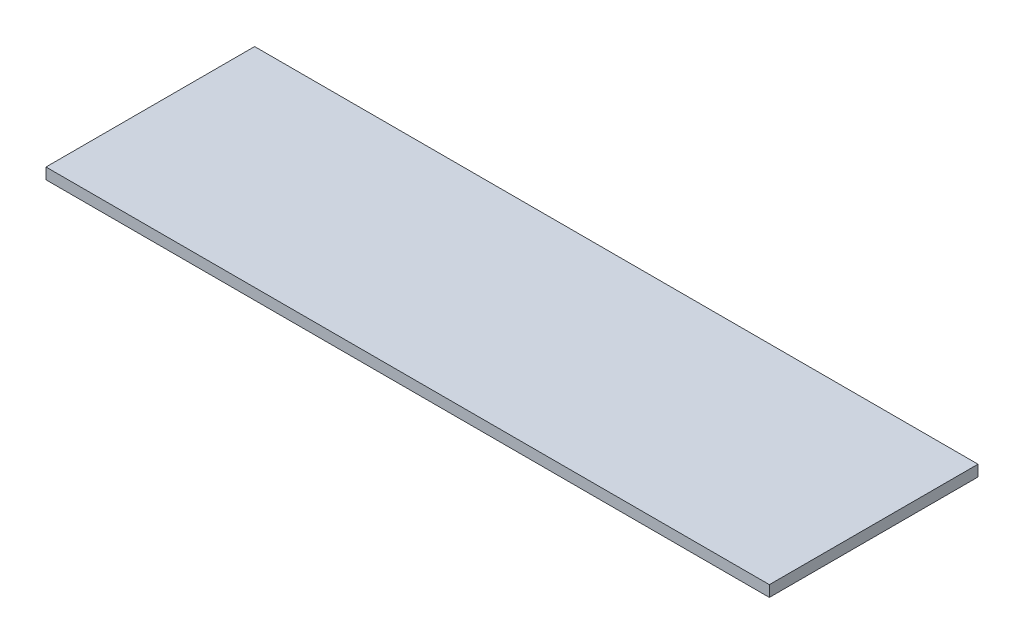
SolidWorks part; units mm, degrees
ref_plane "Front Plane" through (0, 0, 0) normal (0, 0, 1) x (1, 0, 0)
ref_plane "Top Plane" through (0, 0, 0) normal (0, 1, 0) x (1, 0, 0)
ref_plane "Right Plane" through (0, 0, 0) normal (1, 0, 0) x (0, 0, -1)
sketch "Sketch1" plane through (0, 0, 0) normal (0, 1, 0) x (1, 0, 0)
  line L1 (146.5, -42.25) -> (-146.5, -42.25)
  line L2 (146.5, -42.25) -> (146.5, 42.25)
  line L3 (146.5, 42.25) -> (-146.5, 42.25)
  line L4 (-146.5, -42.25) -> (-146.5, 42.25)
  line L5 (146.5, -42.25) -> (-146.5, 42.25) construction
  line L6 (146.5, 42.25) -> (-146.5, -42.25) construction
  point P0 (0, 0)
  dimension "D1" = 293
  dimension "D2" = 84.5
extrude "Boss-Extrude1" add sketch "Sketch1" along normal blind 4.5
sketch "Sketch2" plane through (0, 4.5, 0) normal (0, 1, 0) x (1, 0, 0)
  line L1 (-146.5, 42.25) -> (-137, 42.25) construction
  line L2 (-146.5, 42.25) -> (-146.5, 32.75) construction
  line L3 (-146.5, 32.75) -> (-137, 32.75) construction
  line L4 (146.5, 42.25) -> (137, 42.25) construction
  line L5 (146.5, 42.25) -> (146.5, 32.75) construction
  line L6 (146.5, 32.75) -> (137, 32.75) construction
  line L7 (137, 42.25) -> (137, 32.75) construction
  line L8 (-137, 42.25) -> (-137, 32.75) construction
  circle A0 centre (137, 32.75) radius 1.6
  circle A1 centre (-137, 32.75) radius 1.6
  dimension "D3" = 9.5
  dimension "D1" = 9.5
  dimension "D2" = 9.5
  dimension "D4" = 9.5
extrude "Cut-Extrude2" [suppressed] cut sketch "Sketch2" against normal up to next
